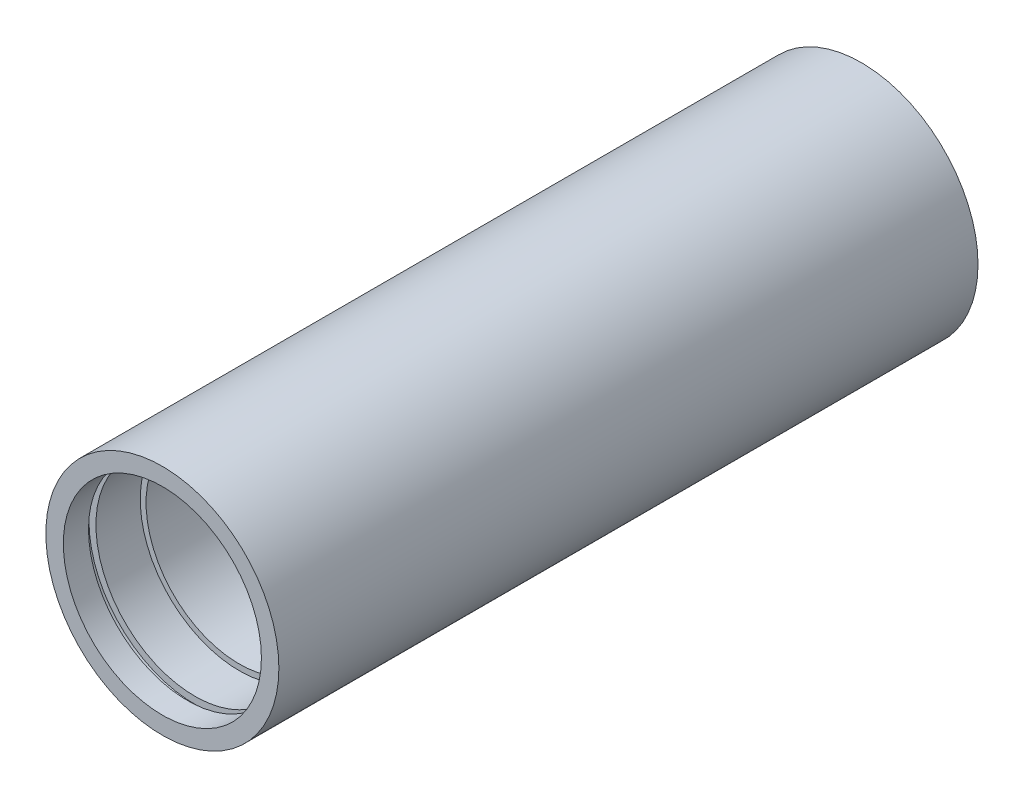
SolidWorks part; units mm, degrees
material "ASTM A36 Steel"
ref_plane "Front Plane" through (0, 0, 0) normal (0, 0, 1) x (1, 0, 0)
ref_plane "Top Plane" through (0, 0, 0) normal (0, 1, 0) x (1, 0, 0)
ref_plane "Right Plane" through (0, 0, 0) normal (1, 0, 0) x (0, 0, -1)
sketch "Sketch1" plane through (0, 0, 0) normal (0, 0, 1) x (1, 0, 0)
  circle A0 centre (0, 0) radius 50
  dimension "D1" = 100
extrude "Boss-Extrude1" add sketch "Sketch1" along normal mid plane 300
sketch "Sketch2" plane through (0, 0, 150) normal (0, 0, 1) x (1, 0, 0)
  circle A0 centre (0, 0) radius 42.5
  dimension "D1" = 85
extrude "Cut-Extrude1" cut sketch "Sketch2" against normal blind 33
sketch "Sketch3" plane through (0, 0, 117) normal (0, 0, 1) x (1, 0, 0)
  circle A0 centre (0, 0) radius 40
  dimension "D1" = 80
extrude "Cut-Extrude2" cut sketch "Sketch3" against normal through all
sketch "Sketch4" plane through (0, 0, 0) normal (0, 1, 0) x (1, 0, 0)
  line L0 (0, -150) -> (0, -235.8251) construction
  line L1 (35.5, -136) -> (45.5, -136)
  line L2 (35.5, -136) -> (35.5, -139.2)
  line L3 (35.5, -139.2) -> (45.5, -139.2)
  line L4 (45.5, -136) -> (45.5, -139.2)
  line L5 (-50, -150) -> (50, -150) construction
  line L6 (-40, -117) -> (40, -117) construction
  dimension "D1" = 3.2
  dimension "D2" = 45.5
  dimension "D3" = 19
  dimension "D4" = 10
revolve "Cut-Revolve1" cut sketch "Sketch4" angle 360 about L0
mirror "Mirror1" about plane through (0, 0, 0) normal (0, 0, 1) of "Cut-Revolve1", "Cut-Extrude2", "Cut-Extrude1"
